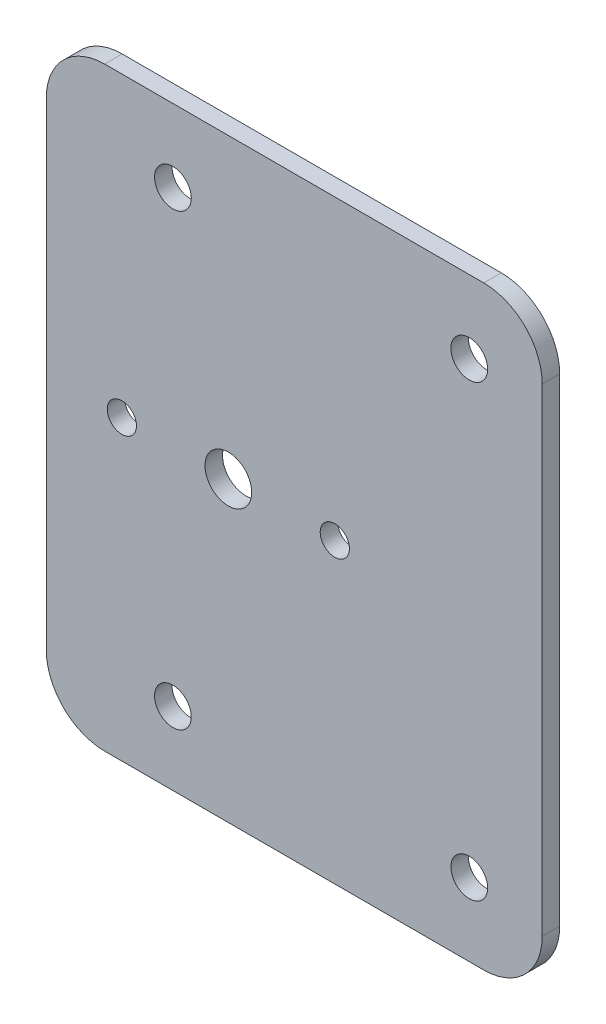
SolidWorks part; units mm, degrees
ref_plane "Front Plane" through (0, 0, 0) normal (0, 0, 1) x (1, 0, 0)
ref_plane "Top Plane" through (0, 0, 0) normal (0, 1, 0) x (1, 0, 0)
ref_plane "Right Plane" through (0, 0, 0) normal (1, 0, 0) x (0, 0, -1)
sketch "Croquis1" plane through (0, 0, 0) normal (0, 0, 1) x (1, 0, 0)
  line L0 (0, 0) -> (0, 50000) construction
  line L1 (0, 0) -> (50000, 0) construction
  line L3 (-31.2, 51) -> (53.8, 51)
  line L4 (-31.2, 51) -> (-31.2, -51)
  line L5 (-31.2, -51) -> (53.8, -51)
  line L6 (53.8, 51) -> (53.8, -51)
  circle A1 centre (0, 0) radius 4
  circle A2 centre (18.25, 0) radius 2.5
  circle A3 centre (-18.25, 0) radius 2.5
  circle A4 centre (-9.5, 38.5) radius 3.15
  circle A7 centre (-9.5, -38.5) radius 3.15
  circle A8 centre (41.3, 38.5) radius 3.15
  circle A9 centre (41.3, -38.5) radius 3.15
  point P14 (-31.2, 0)
  dimension "D1" = 8
  dimension "D2" = 5
  dimension "D3" = 18.25
  dimension "D5" = 53.8
  dimension "D7" = 6.3
  dimension "D8" = 12.5
  dimension "D9" = 9.5
  dimension "D10" = 6.3
  dimension "D11" = 12.5
  dimension "D12" = 12.5
  dimension "D4" = 102
  dimension "D6" = 85
extrude "Saliente-Extruir1" add sketch "Croquis1" along normal blind 3
fillet "Redondeo1" radius 10 4 edges at (-31.2, -51, 1.5) (53.8, -51, 1.5) (-31.2, 51, 1.5) (53.8, 51, 1.5)
